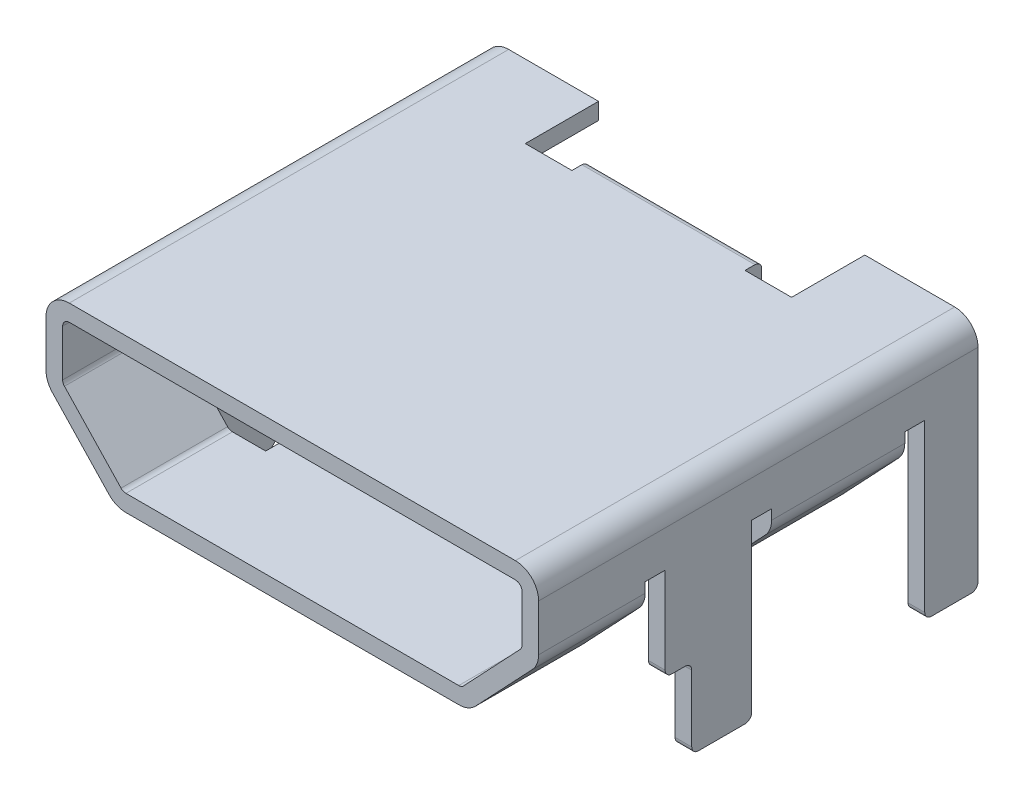
SolidWorks part; units mm, degrees
ref_plane "前视基准面" through (0, 0, 0) normal (0, 0, 1) x (1, 0, 0)
ref_plane "上视基准面" through (0, 0, 0) normal (0, 1, 0) x (1, 0, 0)
ref_plane "右视基准面" through (0, 0, 0) normal (1, 0, 0) x (0, 0, -1)
sketch "草图1" plane through (0, 0, 0) normal (0, 0, 1) x (1, 0, 0)
  line L0 (0, 2.9812) -> (0, -3.1598) construction
  line L1 (4.1649, 0) -> (-4.527, 0) construction
  line L2 (-3.35, 0.9) -> (3.35, 0.9)
  line L3 (3.45, 0.8) -> (3.45, 0.1)
  line L4 (3.4227, 0.0313) -> (2.5727, -0.8687)
  line L5 (2.5, -0.9) -> (-2.5, -0.9)
  line L6 (-2.5727, -0.8687) -> (-3.4227, 0.0313)
  line L7 (-3.45, 0.1) -> (-3.45, 0.8)
  line L8 (-3.35, 1.15) -> (3.35, 1.15)
  line L9 (3.7, 0.8) -> (3.7, 0.1)
  line L10 (3.6045, -0.1403) -> (2.7545, -1.0403)
  line L11 (2.5, -1.15) -> (-2.5, -1.15)
  line L12 (-2.7545, -1.0403) -> (-3.6045, -0.1403)
  line L13 (-3.7, 0.1) -> (-3.7, 0.8)
  arc A0 (-2.5, -0.9) -> (-2.5727, -0.8687) centre (-2.5, -0.8) cw
  arc A1 (2.5, -0.9) -> (2.5727, -0.8687) centre (2.5, -0.8) ccw
  arc A2 (3.4227, 0.0313) -> (3.45, 0.1) centre (3.35, 0.1) ccw
  arc A3 (-3.4227, 0.0313) -> (-3.45, 0.1) centre (-3.35, 0.1) cw
  arc A4 (3.45, 0.8) -> (3.35, 0.9) centre (3.35, 0.8) ccw
  arc A5 (-3.45, 0.8) -> (-3.35, 0.9) centre (-3.35, 0.8) cw
  arc A6 (3.7, 0.8) -> (3.35, 1.15) centre (3.35, 0.8) ccw
  arc A7 (3.6045, -0.1403) -> (3.7, 0.1) centre (3.35, 0.1) ccw
  arc A8 (2.5, -1.15) -> (2.7545, -1.0403) centre (2.5, -0.8) ccw
  arc A9 (-2.5, -1.15) -> (-2.7545, -1.0403) centre (-2.5, -0.8) cw
  arc A10 (-3.6045, -0.1403) -> (-3.7, 0.1) centre (-3.35, 0.1) cw
  arc A11 (-3.7, 0.8) -> (-3.35, 1.15) centre (-3.35, 0.8) cw
  dimension "D3" = 0.1
  dimension "D1" = 6.9
  dimension "D2" = 1.8
  dimension "D4" = 0.8
  dimension "D5" = 5
  dimension "D6" = 0.25
extrude "凸台-拉伸1" add sketch "草图1" along normal blind 6.6
sketch "草图2" plane through (0, -1.15, 0) normal (0, -1, 0) x (1, 0, 0)
  line L0 (-2.5, 0) -> (2.5, 0) construction
  line L1 (2, 0) -> (-2, 0)
  line L2 (2, 0) -> (2, 1.1)
  line L3 (2, 1.1) -> (-2, 1.1)
  line L4 (-2, 0) -> (-2, 1.1)
  line L5 (0, 0) -> (0, -4.9774) construction
  line L6 (-2.5, 6.6) -> (2.5, 6.6) construction
  dimension "D1" = 5.5
  dimension "D2" = 4
extrude "切除-拉伸1" cut sketch "草图2" against normal blind 6.6
ref_plane "基准面1" through (0, 0, 1.1) normal (0, 0, -1) x (-1, 0, 0)
sketch "草图3" plane through (0, 0, 1.1) normal (0, 0, -1) x (-1, 0, 0)
  line L6 (2.5727, -0.8687) -> (3.4227, 0.0313)
  line L7 (3.45, 0.1) -> (3.45, 0.8)
  line L8 (3.35, 0.9) -> (-3.35, 0.9)
  line L9 (-3.45, 0.8) -> (-3.45, 0.1)
  line L10 (-3.4227, 0.0313) -> (-2.5727, -0.8687)
  line L11 (-2.5, -0.9) -> (2.5, -0.9)
  line L12 (2.5727, -0.8687) -> (3.4227, 0.0313)
  line L13 (3.45, 0.1) -> (3.45, 0.8)
  line L14 (3.35, 0.9) -> (-3.35, 0.9)
  line L15 (-3.45, 0.8) -> (-3.45, 0.1)
  line L16 (-3.4227, 0.0313) -> (-2.5727, -0.8687)
  line L17 (-2.5, -0.9) -> (2.5, -0.9)
  arc A6 (2.5, -0.9) -> (2.5727, -0.8687) centre (2.5, -0.8) ccw
  arc A7 (3.4227, 0.0313) -> (3.45, 0.1) centre (3.35, 0.1) ccw
  arc A8 (3.45, 0.8) -> (3.35, 0.9) centre (3.35, 0.8) ccw
  arc A9 (-3.35, 0.9) -> (-3.45, 0.8) centre (-3.35, 0.8) ccw
  arc A10 (-3.45, 0.1) -> (-3.4227, 0.0313) centre (-3.35, 0.1) ccw
  arc A11 (-2.5727, -0.8687) -> (-2.5, -0.9) centre (-2.5, -0.8) ccw
  arc A12 (2.5, -0.9) -> (2.5727, -0.8687) centre (2.5, -0.8) ccw
  arc A13 (3.4227, 0.0313) -> (3.45, 0.1) centre (3.35, 0.1) ccw
  arc A14 (3.45, 0.8) -> (3.35, 0.9) centre (3.35, 0.8) ccw
  arc A15 (-3.35, 0.9) -> (-3.45, 0.8) centre (-3.35, 0.8) ccw
  arc A16 (-3.45, 0.1) -> (-3.4227, 0.0313) centre (-3.35, 0.1) ccw
  arc A17 (-2.5727, -0.8687) -> (-2.5, -0.9) centre (-2.5, -0.8) ccw
  dimension "D1" = 0
extrude "凸台-拉伸2" add sketch "草图3" against normal blind 1
sketch "草图4" plane through (0, 0, 2.1) normal (0, 0, 1) x (1, 0, 0)
  line L0 (-3.35, 0.9) -> (3.35, 0.9) construction
  line L1 (-1.7, 0.6) -> (1.7, 0.6)
  line L2 (-1.7, 0.6) -> (-1.7, 0.2)
  line L3 (-1.7, 0.2) -> (1.7, 0.2)
  line L4 (1.7, 0.6) -> (1.7, 0.2)
  line L5 (0, 0) -> (0, 2.0131) construction
  dimension "D1" = 0.4
  dimension "D2" = 0.3
  dimension "D3" = 3.4
extrude "凸台-拉伸3" add sketch "草图4" along normal offset from surface (3.9 mm away) 0.6 up to face at (0, -0.0406, 6.6)
chamfer "倒角1" distance 0.1 angle 60 1 edges at (0, 0.2, 6)
sketch "草图5" plane through (0, -1.15, 0) normal (0, -1, 0) x (1, 0, 0)
  line L0 (0, 0) -> (0, 8.4174) construction
  line L1 (4, -0.4) -> (-4, -0.4)
  line L2 (4, -0.4) -> (4, 1.1)
  line L3 (4, 1.1) -> (-4, 1.1)
  line L4 (-4, -0.4) -> (-4, 1.1)
  line L5 (4, 3.1) -> (2, 3.1)
  line L6 (4, 3.1) -> (4, 5)
  line L7 (4, 5) -> (2, 5)
  line L8 (2, 3.1) -> (2, 5)
  line L9 (-2, 3.1) -> (-4, 3.1)
  line L10 (-2, 3.1) -> (-2, 5)
  line L11 (-2, 5) -> (-4, 5)
  line L12 (-4, 3.1) -> (-4, 5)
  line L13 (-2.5, 6.6) -> (2.5, 6.6) construction
  line L14 (-1.5066, 1.1) -> (1.5066, 1.1) construction
  dimension "D1" = 2
  dimension "D2" = 2
  dimension "D3" = 1.9
  dimension "D4" = 1.6
  dimension "D5" = 1.5
  dimension "D6" = 8
extrude "切除-拉伸2" cut sketch "草图5" against normal blind 1.4
sketch "草图6" plane through (0, 0.25, 0) normal (0, -1, 0) x (1, 0, 0)
  line L0 (3.45, 0) -> (3.45, 1.1) construction
  line L1 (3.7, 0) -> (3.45, 0)
  line L2 (3.7, 0) -> (3.7, 0.8)
  line L3 (3.7, 0.8) -> (3.45, 0.8)
  line L4 (3.45, 0) -> (3.45, 0.8)
  line L5 (3.7, 3.1) -> (3.7, 5) construction
  line L6 (3.7, 3.4) -> (3.45, 3.4)
  line L7 (3.7, 3.4) -> (3.7, 4.3)
  line L8 (3.7, 4.3) -> (3.45, 4.3)
  line L9 (3.45, 3.4) -> (3.45, 4.3)
  line L10 (3.45, 6.6) -> (3.45, 2.1) construction
  line L11 (0, 0) -> (0, 5.3173) construction
  line L12 (4.0566, 3.85) -> (0, 3.85) construction
  line L16 (-3.7, 4.3) -> (-3.45, 4.3)
  line L17 (-3.7, 3.4) -> (-3.7, 4.3)
  line L18 (-3.45, 3.4) -> (-3.45, 4.3)
  line L19 (-3.7, 3.4) -> (-3.45, 3.4)
  line L20 (-3.7, 0.8) -> (-3.45, 0.8)
  line L21 (-3.7, 0) -> (-3.7, 0.8)
  line L22 (-3.7, 0) -> (-3.45, 0)
  line L23 (-3.45, 0) -> (-3.45, 0.8)
  line L24 (-2.5, 6.6) -> (2.5, 6.6) construction
  dimension "D1" = 0.8
  dimension "D2" = 2.75
  dimension "D3" = 0.9
extrude "凸台-拉伸5" add sketch "草图6" along normal offset from surface (2.6 mm away) 3.5 up to face at (0, 1.15, 1.925)
sketch "草图7" plane through (0, 0.25, 0) normal (0, -1, 0) x (1, 0, 0)
  line L0 (3.45, 6.6) -> (3.45, 2.1) construction
  line L1 (3.7, 4.3) -> (3.45, 4.3)
  line L2 (3.7, 4.3) -> (3.7, 4.7)
  line L3 (3.7, 4.7) -> (3.45, 4.7)
  line L4 (3.45, 4.3) -> (3.45, 4.7)
  line L6 (4.5535, 4.05) -> (0.704, 4.05) construction
  line L7 (2, 3.1) -> (2.5, 3.1) construction
  line L8 (2.5, 5) -> (2, 5) construction
  line L9 (3.45, 3.4) -> (3.7, 3.4) construction
  line L13 (3.45, 3.4) -> (3.7, 3.4) construction
  line L15 (0, 0) -> (0, 4.6085) construction
  line L16 (-3.45, 4.3) -> (-3.45, 4.7)
  line L17 (-3.7, 4.7) -> (-3.45, 4.7)
  line L18 (-3.7, 4.3) -> (-3.7, 4.7)
  line L19 (-3.7, 4.3) -> (-3.45, 4.3)
extrude "凸台-拉伸6" add sketch "草图7" along normal up to surface (1.4 mm away) up to face at (0, -1.15, 3.9833)
ref_plane "基准面2" through (0, 0, 1.4) normal (0, 0, -1) x (-1, 0, 0)
sketch "草图8" plane through (0, 0, 1.4) normal (0, 0, -1) x (-1, 0, 0)
  line L0 (0, 0) -> (0, -3.4788) construction
  line L1 (-1.3, -0.9366) -> (-1.3, -1.4134) construction
  line L3 (-0.8, -1.1) -> (-0.5, -1.1)
  line L4 (-0.8, -1.1) -> (-0.8, -1.3)
  line L5 (-0.8, -1.3) -> (-0.5, -1.3)
  line L6 (-0.5, -1.1) -> (-0.5, -1.3)
  line L7 (-0.15, -1.1) -> (0.15, -1.1)
  line L8 (-0.15, -1.1) -> (-0.15, -1.3)
  line L9 (-0.15, -1.3) -> (0.15, -1.3)
  line L10 (0.15, -1.1) -> (0.15, -1.3)
  line L11 (0.5, -1.1) -> (0.8, -1.1)
  line L12 (0.5, -1.1) -> (0.5, -1.3)
  line L13 (0.5, -1.3) -> (0.8, -1.3)
  line L14 (0.8, -1.1) -> (0.8, -1.3)
  line L15 (1.15, -1.1) -> (1.45, -1.1)
  line L16 (1.15, -1.1) -> (1.15, -1.3)
  line L17 (1.15, -1.3) -> (1.45, -1.3)
  line L18 (1.45, -1.1) -> (1.45, -1.3)
  line L19 (-2.5, -1.15) -> (2.5, -1.15) construction
  line L34 (-1.15, -1.1) -> (-1.15, -1.3)
  line L35 (-1.45, -1.3) -> (-1.15, -1.3)
  line L36 (-1.45, -1.1) -> (-1.15, -1.1)
  line L37 (-1.45, -1.1) -> (-1.45, -1.3)
  dimension "D1" = 0.3
  dimension "D2" = 0.2
  dimension "D3" = 1.3
  dimension "D5" = 0.15
  dimension "D4" = 5
extrude "凸台-拉伸7" add sketch "草图8" along normal up to surface (1.4 mm away) up to face at (3.1366, 0.1366, 0)
sketch "草图9" plane through (0, 0.2, 0) normal (0, -1, 0) x (1, 0, 0)
  line L0 (-1.45, 2.1) -> (-1.45, 5.8)
  line L1 (-1.7, 2.1) -> (1.7, 2.1) construction
  line L2 (-1.45, 5.8) -> (-1.15, 5.8)
  line L3 (-1.15, 5.8) -> (-1.15, 2.1)
  line L4 (-1.45, 0) -> (-1.45, 1.4) construction
  line L5 (-1.15, 0) -> (-1.15, 1.4) construction
  line L6 (-2.5, 6.6) -> (2.5, 6.6) construction
  line L7 (-1.45, 2.1) -> (-1.15, 2.1)
  line L8 (-0.5, 5.8) -> (-0.5, 2.1)
  line L9 (-0.8, 2.1) -> (-0.8, 5.8)
  line L10 (-0.8, 5.8) -> (-0.5, 5.8)
  line L11 (-0.8, 2.1) -> (-0.5, 2.1)
  line L12 (0.15, 5.8) -> (0.15, 2.1)
  line L13 (-0.15, 2.1) -> (-0.15, 5.8)
  line L14 (-0.15, 5.8) -> (0.15, 5.8)
  line L15 (-0.15, 2.1) -> (0.15, 2.1)
  line L16 (0.8, 5.8) -> (0.8, 2.1)
  line L17 (0.5, 2.1) -> (0.5, 5.8)
  line L18 (0.5, 5.8) -> (0.8, 5.8)
  line L19 (0.5, 2.1) -> (0.8, 2.1)
  line L20 (1.45, 5.8) -> (1.45, 2.1)
  line L21 (1.15, 2.1) -> (1.15, 5.8)
  line L22 (1.15, 5.8) -> (1.45, 5.8)
  line L23 (1.15, 2.1) -> (1.45, 2.1)
  dimension "D1" = 0.8
  dimension "D2" = 5
extrude "凸台-拉伸8" add sketch "草图9" along normal blind 0.01
sketch "草图10" plane through (0, 0, 1.1) normal (0, 0, -1) x (-1, 0, 0)
  line L0 (-2, 1.15) -> (2, 1.15) construction
  line L1 (-1.3, 1.15) -> (1.3, 1.15)
  line L2 (-1.3, 1.15) -> (-1.3, -0.45)
  line L3 (-1.3, -0.45) -> (1.3, -0.45)
  line L4 (1.3, 1.15) -> (1.3, -0.45)
  line L5 (0, 0) -> (0, 1.982) construction
  dimension "D1" = 2.6
  dimension "D2" = 1.6
extrude "凸台-拉伸9" add sketch "草图10" along normal blind 0.25
fillet "圆角1" radius 0.1 13 edges at (-3.575, -2.35, 0.8) (-3.575, -2.35, 0) (3.575, -2.35, 0) (3.575, -2.35, 0.8) (-3.575, -2.35, 3.4) (-3.575, -2.35, 4.3) (-3.575, -1.15, 4.3) (-3.575, -1.15, 4.7) (3.575, -2.35, 3.4) (3.575, -2.35, 4.3) (3.575, -1.15, 4.3) (3.575, -1.15, 4.7) (0, 1.15, 0.85)
